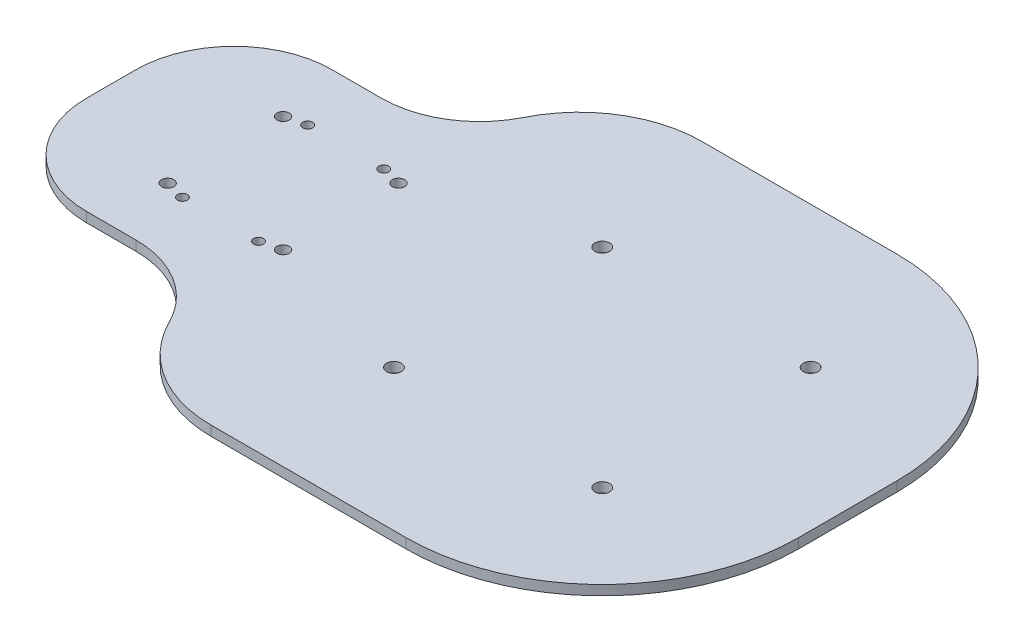
SolidWorks part; units mm, degrees
material "1060 Alloy"
ref_plane "Front Plane" through (0, 0, 0) normal (0, 0, 1) x (1, 0, 0)
ref_plane "Top Plane" through (0, 0, 0) normal (0, 1, 0) x (1, 0, 0)
ref_plane "Right Plane" through (0, 0, 0) normal (1, 0, 0) x (0, 0, -1)
sketch "Sketch1" plane through (0, 0, 0) normal (0, 1, 0) x (1, 0, 0)
  line L1 (-100, 100) -> (100, 100)
  line L2 (-100, 100) -> (-100, 50)
  line L3 (-100, -100) -> (100, -100)
  line L4 (100, 100) -> (100, -100)
  line L5 (-100, -50) -> (-100, -100)
  line L7 (-100, -50) -> (-200, -50)
  line L8 (-100, 50) -> (-200, 50)
  line L9 (-200, -50) -> (-200, 50)
  dimension "D2" = 200
  dimension "D3" = 200
  dimension "D4" = 100
  dimension "D5" = 100
  dimension "D6" = 50
extrude "Boss-Extrude1" add sketch "Sketch1" along normal blind 4
fillet "Fillet1" radius 40 4 edges at (-100, 2, -50) (-200, 2, -50) (-200, 2, 50) (-100, 2, 50)
sketch "Sketch2" plane through (0, 4, 0) normal (0, 1, 0) x (1, 0, 0)
  circle A0 centre (42.425, 42.425) radius 3
  circle A1 centre (42.425, -42.425) radius 3
  circle A2 centre (-42.425, -42.425) radius 3
  circle A3 centre (-42.425, 42.425) radius 3
  point P0 (0, 0)
  dimension "D3" = 6
  dimension "D1" = 84.85
  dimension "D2" = 84.85
extrude "Cut-Extrude1" cut sketch "Sketch2" against normal blind 4
sketch "Sketch3" plane through (0, 4, 0) normal (0, 1, 0) x (1, 0, 0)
  line L0 (0, 0) -> (-220.1179, 0) construction
  line L6 (-145.5, 25.5) -> (-114.5, -25.5) construction
  line L7 (-145.5, -25.5) -> (-114.5, 25.5) construction
  circle A0 centre (-114.5, -25.5) radius 2
  circle A1 centre (-106.5, 23.5) radius 2.5
  circle A2 centre (-153.5, 23.5) radius 2.5
  circle A3 centre (-153.5, -23.5) radius 2.5
  circle A4 centre (-106.5, -23.5) radius 2.5
  circle A5 centre (-145.5, -25.5) radius 2
  circle A6 centre (-145.5, 25.5) radius 2
  circle A7 centre (-114.5, 25.5) radius 2
  point P1 (-130, 0)
  point P3 (-130, 0)
  point P4 (-130, 0)
  point P5 (-130, 0)
  dimension "D4" = 5
  dimension "D5" = 31
  dimension "D6" = 4
  dimension "D1" = 51
  dimension "D2" = 47
  dimension "D3" = 47
extrude "Cut-Extrude2" cut sketch "Sketch3" against normal blind 4
fillet "Fillet2" radius 80 2 edges at (100, 2, -100) (100, 2, 100)
fillet "Fillet3" radius 50 2 edges at (-100, 2, -100) (-100, 2, 100)
